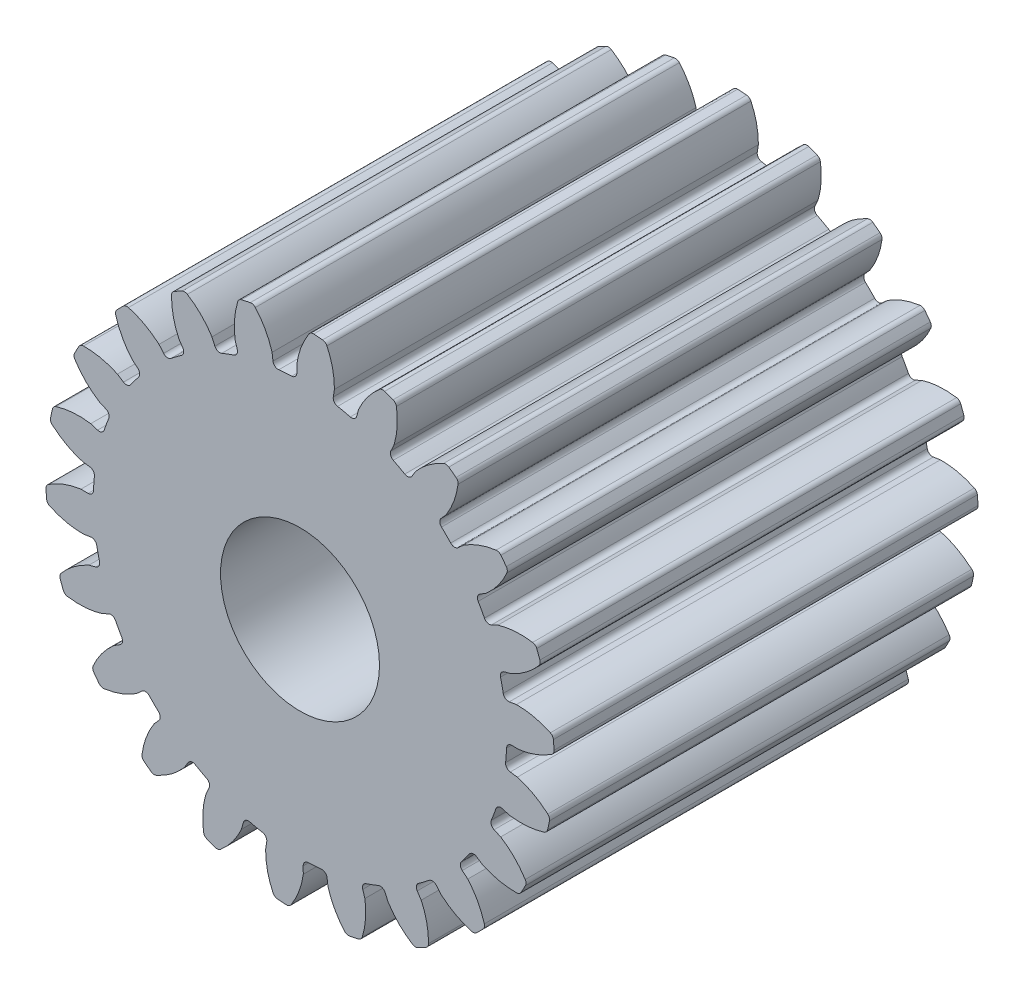
SolidWorks part; units mm, degrees
material "Нержавеющая сталь (ферритная)"
ref_plane "Спереди" through (0, 0, 0) normal (0, 0, 1) x (1, 0, 0)
ref_plane "Сверху" through (0, 0, 0) normal (0, 1, 0) x (1, 0, 0)
ref_plane "Справа" through (0, 0, 0) normal (1, 0, 0) x (0, 0, -1)
sketch "Эскиз1" plane through (0, 0, 0) normal (0, 0, 1) x (1, 0, 0)
  circle A0 centre (0, 0) radius 3.9
  circle A1 centre (0, 0) radius 1.5
  dimension "D1" = 7.8
  dimension "D2" = 3
extrude "Бобышка-Вытянуть1" add sketch "Эскиз1" along normal mid plane 8
sketch "Эскиз2" plane through (0, 0, 0) normal (0, 0, 1) x (1, 0, 0)
  line L0 (0, 0) -> (0, 4.4) construction
  line L1 (0, 4.4) -> (0.6174, 4.4) construction
  line L2 (0, 4.4) -> (1.4141, 3.8853) construction
  line L3 (2.2478, 3.4702) -> (0.2015, 4.7958) construction
  line L4 (0, 0) -> (-0.0616, 4.1342) construction
  line L5 (-0.0616, 4.1342) -> (-0.0581, 3.8996)
  line L6 (0, 0) -> (0.3424, 4.7878) construction
  line L7 (0.6494, 4.0833) -> (0.6125, 3.8516)
  arc A0 (0.4831, 4.7756) -> (0.2015, 4.7958) centre (0, 0) ccw
  circle A1 centre (0, 0) radius 4.4 construction
  circle A2 centre (0, 0) radius 3.9 construction
  arc A3 (0.6125, 3.8516) -> (-0.0581, 3.8996) centre (0, 0) ccw
  circle A4 centre (0, 0) radius 4.1346 construction
  spline S0 degree 2 poles (-0.0616, 4.1342) (-0.0117, 4.4947) (0.2015, 4.7958) knots 0 0 0 1 1 1
  spline S1 degree 2 poles (0.6494, 4.0833) (0.6513, 4.4473) (0.4831, 4.7756) knots 0 0 0 1 1 1
  point P1 (0.6181, 4.3969)
  point P2 (1.4141, 3.8853)
  point P10 (1.4141, 3.8853)
  point P11 (-0.0616, 4.1342)
  dimension "D1" = 8.8
  dimension "D2" = 9.6
  dimension "D3" = 20
  dimension "D4" = 1.5049
  dimension "D6" = 2.4382
  dimension "D8" = 4.091
  dimension "D5" = 1.5049
  dimension "D7" = 0.9333
extrude "Бобышка-Вытянуть2" add sketch "Эскиз2" along normal mid plane 8
fillet "Скругление1" radius 0.1 4 edges at (-0.0581, 3.8996, 0) (0.6125, 3.8516, 0) (0.4831, 4.7756, 0) (0.2015, 4.7958, 0)
pattern_circular "Круговой массив1" count 22 over 360 about axis through (0, 0, 4) along (0, 0, -1) of "Бобышка-Вытянуть2", "Скругление1"
equation "\"Число зубьев\"= 22"
equation "\"Модуль\"= 0.4мм"
equation "\"D1@Эскиз1\"= \"Модуль\" * (\"Число зубьев\" - 2.5)"
equation "\"D1@Эскиз2\"= \"Модуль\" * \"Число зубьев\""
equation "\"D5@Эскиз2\"= \"D4@Эскиз2\""
equation "\"D7@Эскиз2\"= \"D6@Эскиз2\" - \"D4@Эскиз2\""
equation "\"D8@Эскиз2\"= 90 / \"Число зубьев\""
equation "\"D1@Круговой массив1\"= \"Число зубьев\""
